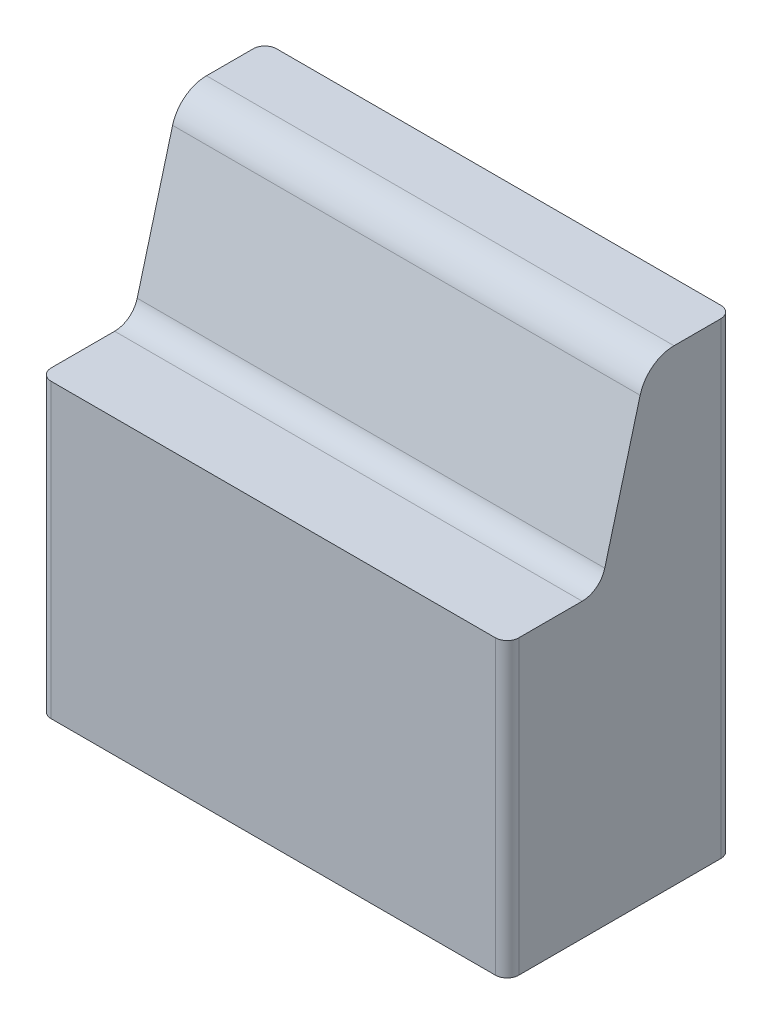
SolidWorks part; units mm, degrees
material "K110"
ref_plane "Front Plane" through (0, 0, 0) normal (0, 0, 1) x (1, 0, 0)
ref_plane "Top Plane" through (0, 0, 0) normal (0, 1, 0) x (1, 0, 0)
ref_plane "Right Plane" through (0, 0, 0) normal (1, 0, 0) x (0, 0, -1)
sketch "Sketch1" plane through (0, 0, 0) normal (1, 0, 0) x (0, 0, -1)
  line L0 (-5, 0) -> (0, 0)
  line L1 (0, 0) -> (0, -40)
  line L2 (0, -40) -> (-19.28, -40)
  line L3 (-19.28, -40) -> (-19.28, -15)
  line L4 (-19.28, -15) -> (-11.3212, -15)
  line L5 (-11.3212, -15) -> (-7.8978, -2.2235)
  arc A0 (-7.8978, -2.2235) -> (-5, 0) centre (-5, -3) cw
  dimension "D2" = 3
  dimension "D1" = 5
  dimension "D3" = 40
  dimension "D4" = 25
  dimension "D5" = 75
  dimension "D6" = 19.28
extrude "Boss-Extrude1" add sketch "Sketch1" along normal mid plane 40
fillet "Fillet1" radius 1 4 edges at (-20, -20, 0) (-20, -27.5, 19.28) (20, -20, 0) (20, -27.5, 19.28)
hole_wizard "M6 Tapped Hole1" positions "Sketch5" profile "Sketch3" tap size "M6" standard "ISO"
sketch "Sketch5" plane through (0, -40, 0) normal (0, -1, 0) x (-1, 0, 0)
  line L0 (-19, 0) -> (19, 0) construction
  line L1 (-20, -18.28) -> (-20, -1) construction
  line L2 (20, -18.28) -> (20, -1) construction
  point P0 (-12.5, -7.5)
  point P2 (12.5, -7.5)
  dimension "D1" = 7.5
  dimension "D2" = 7.5
  dimension "D3" = 7.5
sketch "Sketch3" plane through (12.5, -40, 7.5) normal (1, 0, 0) x (0, 0, -1)
  line L0 (0, 0) -> (0, 18.5022)
  line L1 (0, 18.5022) -> (2.5, 17)
  line L2 (2.5, 17) -> (2.5, 0.525)
  line L3 (2.5, 0.525) -> (3.025, 0)
  line L5 (3.025, 0) -> (0, 0)
  line L6 (-2.5, 0.525) -> (-3.025, 0) construction
  line L10 (0, 18.5022) -> (-2.5, 17) construction
  line L11 (0, -6.35) -> (0, 107.95) construction
  dimension "Tap Drill Dia." = 5
  dimension "Tap Drill Depth" = 17
  dimension "Near C'Sink Dia." = 6.05
  dimension "Near C'Sink Angle" = 90
  dimension "Drill Angle" = 118
cosmetic thread "Hole Thread1" parameters "D1"=12, "D2"=6
cosmetic thread "Hole Thread2" parameters "D1"=12, "D2"=6
fillet "Fillet2" radius 2 1 edges at (0, -15, 11.3212)
